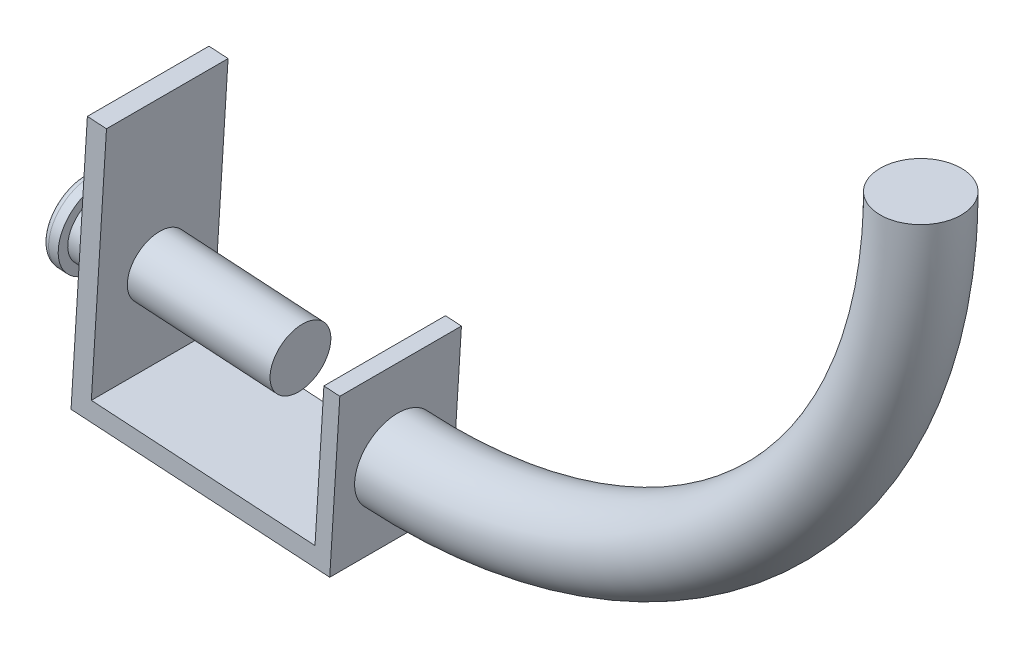
SolidWorks part; units mm, degrees
ref_plane "Front Plane" through (0, 0, 0) normal (0, 0, 1) x (1, 0, 0)
ref_plane "Top Plane" through (0, 0, 0) normal (0, 1, 0) x (1, 0, 0)
ref_plane "Right Plane" through (0, 0, 0) normal (1, 0, 0) x (0, 0, -1)
sketch "Sketch47" plane through (0, 0, 0) normal (0, 0, 1) x (1, 0, 0)
  arc A0 (-9.6441, -154.6997) -> (155, 0) centre (0, 0) ccw
  point P4 (0, 0)
  point P5 (0, 0)
  point P6 (0, 0)
  dimension "D1" = 155
sweep "Sweep5" add path "Sketch47" circular profile diameter 25.4 parameters "D3"=25.4
sketch "Sketch70" plane through (0, 0, 0) normal (-0.9981, 0.0622, 0) x (0, 0, 1)
  line L1 (-19.05, -127.7278) -> (19.05, -127.7278)
  line L2 (-19.05, -127.7278) -> (-19.05, -178.5278)
  line L3 (-19.05, -178.5278) -> (19.05, -178.5278)
  line L4 (19.05, -127.7278) -> (19.05, -178.5278)
  circle A0 centre (0, -155) radius 12.7 construction
  dimension "D4" = 23.5278
  dimension "D1" = 50.8
  dimension "D2" = 38.1
  dimension "D3" = 6.35
extrude "Boss-Extrude1" add sketch "Sketch70" along normal blind 5
sketch "Sketch71" plane through (-4.9903, 0.3111, 0) normal (-0.9981, 0.0622, 0) x (0, 0, 1)
  line L0 (-19.05, -127.7278) -> (-19.05, -178.5278) construction
  line L1 (-19.05, -172.5278) -> (19.05, -172.5278)
  line L2 (-19.05, -172.5278) -> (-19.05, -178.5278)
  line L3 (-19.05, -178.5278) -> (19.05, -178.5278)
  line L4 (19.05, -172.5278) -> (19.05, -178.5278)
  line L5 (-19.05, -178.5278) -> (19.05, -178.5278) construction
  line L6 (19.05, -178.5278) -> (19.05, -127.7278) construction
  dimension "D1" = 6
extrude "Boss-Extrude2" add sketch "Sketch71" along normal blind 76.2
sketch "Sketch72" plane through (-10.7347, -172.1935, 0) normal (0.0622, 0.9981, 0) x (0.9981, -0.0622, 0)
  line L0 (-81.2, -19.05) -> (-5, -19.05) construction
  line L1 (-75.2, -19.05) -> (-81.2, -19.05)
  line L2 (-75.2, -19.05) -> (-75.2, 19.05)
  line L3 (-75.2, 19.05) -> (-81.2, 19.05)
  line L4 (-81.2, -19.05) -> (-81.2, 19.05)
  dimension "D1" = 6
extrude "Boss-Extrude3" add sketch "Sketch72" along normal blind 76.2
sketch "Sketch73" plane through (-81.0427, 5.0523, 0) normal (-0.9981, 0.0622, 0) x (0, 0, 1)
  circle A0 centre (0, -144.4874) radius 9.5091
extrude "Boss-Extrude4" add sketch "Sketch73" along normal blind 12.7 and the other way blind 50.8
sketch "Sketch74" plane through (-93.7181, 5.8425, 0) normal (-0.9981, 0.0622, 0) x (0, 0, 1)
  circle A0 centre (0, -144.4874) radius 12.5
  circle A1 centre (0, -144.4874) radius 9.5091 construction
  dimension "D1" = 25
extrude "Boss-Extrude5" add sketch "Sketch74" along normal blind 5 contours A0
fillet "Fillet1" radius 2 1 edges at (-108.4762, -150.5297, 0)
